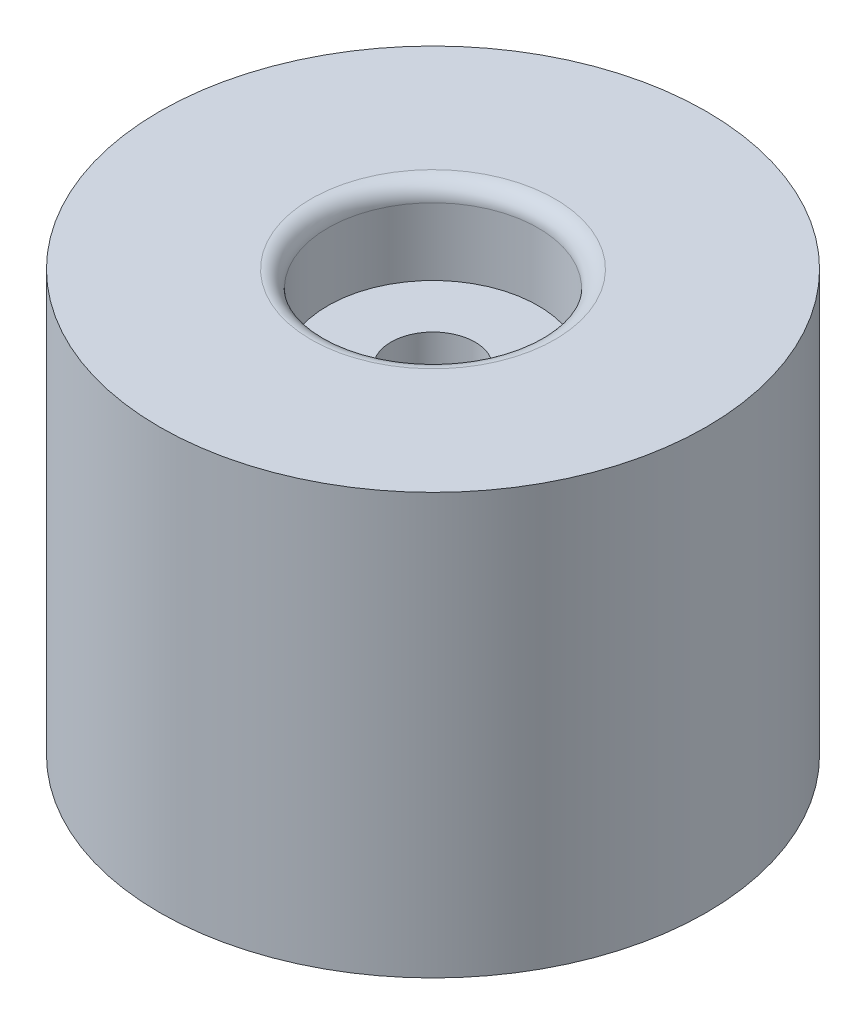
SolidWorks part; units mm, degrees
material "Custom PLA"
ref_plane "Front Plane" through (0, 0, 0) normal (0, 0, 1) x (1, 0, 0)
ref_plane "Top Plane" through (0, 0, 0) normal (0, 1, 0) x (1, 0, 0)
ref_plane "Right Plane" through (0, 0, 0) normal (1, 0, 0) x (0, 0, -1)
sketch "Sketch1" plane through (0, 0, 0) normal (0, 1, 0) x (1, 0, 0)
  line L1 (5.05, -2.9156) -> (5.05, 2.9156)
  line L2 (5.05, 2.9156) -> (0, 5.8312)
  line L3 (0, 5.8312) -> (-5.05, 2.9156)
  line L4 (-5.05, 2.9156) -> (-5.05, -2.9156)
  line L5 (-5.05, -2.9156) -> (0, -5.8312)
  line L6 (0, -5.8312) -> (5.05, -2.9156)
  circle A0 centre (0, 0) radius 5.05 construction
  circle A1 centre (0, 0) radius 6.5
  dimension "D2" = 13
  dimension "D1" = 10.1
extrude "Boss-Extrude1" add sketch "Sketch1" along normal blind 6
sketch "Sketch3" plane through (0, 6, 0) normal (0, 1, 0) x (1, 0, 0)
  circle A0 centre (0, 0) radius 6.5
  circle A1 centre (0, 0) radius 6.5 construction
  circle A2 centre (0, 0) radius 1
  dimension "D1" = 2
extrude "Boss-Extrude2" add sketch "Sketch3" along normal blind 4
sketch "Sketch4" plane through (0, 10, 0) normal (0, 1, 0) x (1, 0, 0)
  circle A0 centre (0, 0) radius 2.5
  dimension "D1" = 5
extrude "Cut-Extrude1" cut sketch "Sketch4" against normal blind 2
fillet "Fillet1" radius 0.4 1 edges at (0, 10, 2.5)
